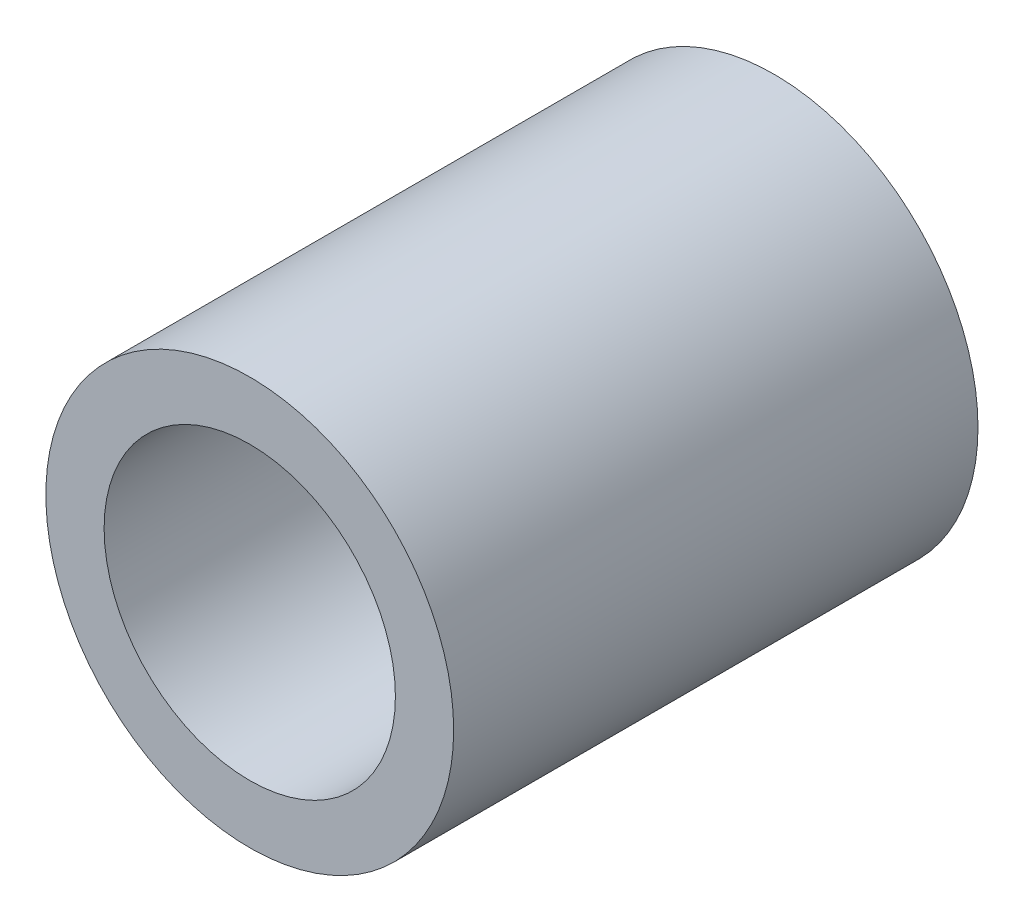
SolidWorks part; units mm, degrees
ref_plane "前视基准面" through (0, 0, 0) normal (0, 0, 1) x (1, 0, 0)
ref_plane "上视基准面" through (0, 0, 0) normal (0, 1, 0) x (1, 0, 0)
ref_plane "右视基准面" through (0, 0, 0) normal (1, 0, 0) x (0, 0, -1)
sketch "Sketch1" plane through (0, 0, 0) normal (0, 0, 1) x (1, 0, 0)
  circle A0 centre (0, 0) radius 2.5
  circle A1 centre (0, 0) radius 3.5
extrude "Boss-Extrude1" add sketch "Sketch1" along normal blind 9
